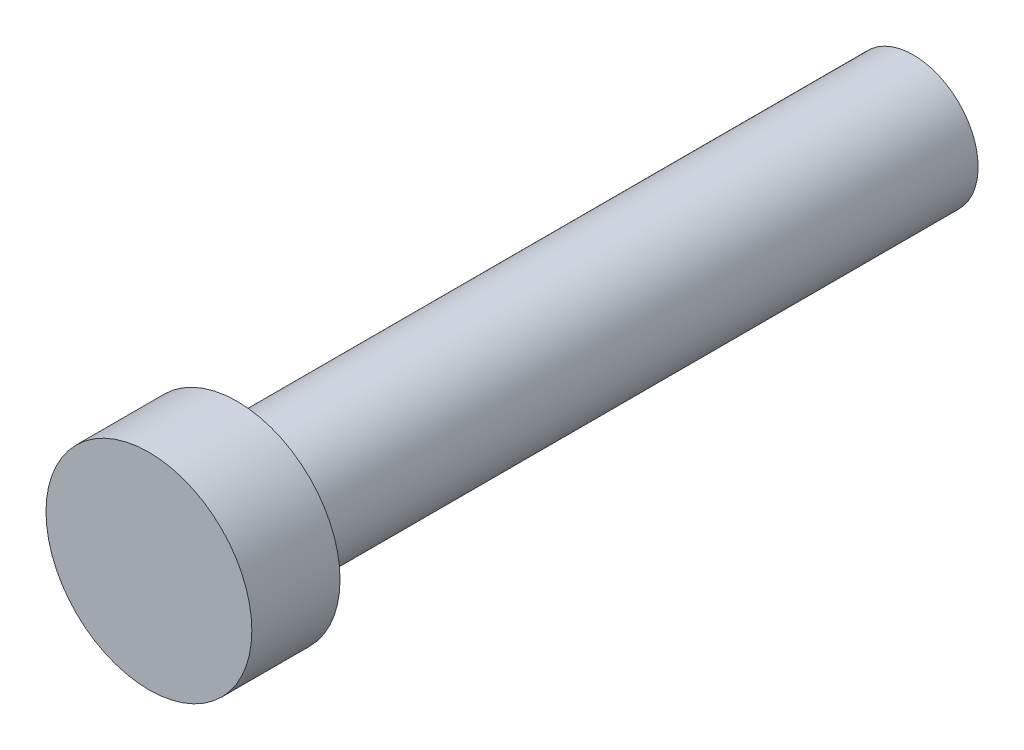
SolidWorks part; units mm, degrees
ref_plane "Front Plane" through (0, 0, 0) normal (0, 0, 1) x (1, 0, 0)
ref_plane "Top Plane" through (0, 0, 0) normal (0, 1, 0) x (1, 0, 0)
ref_plane "Right Plane" through (0, 0, 0) normal (1, 0, 0) x (0, 0, -1)
sketch "Sketch1" plane through (0, 0, 0) normal (0, 0, 1) x (1, 0, 0)
  circle A0 centre (0, 0) radius 2.2
  dimension "D1" = 4.4
extrude "Boss-Extrude1" add sketch "Sketch1" along normal blind 26
sketch "Sketch2" plane through (0, 0, 26) normal (0, 0, 1) x (1, 0, 0)
  circle A0 centre (0, 0) radius 3.5
  dimension "D1" = 7
extrude "Boss-Extrude2" add sketch "Sketch2" against normal blind 3
sketch "Sketch3" plane through (0, 0, 0) normal (0, 0, -1) x (-1, 0, 0)
  circle A0 centre (0, 0) radius 1
  dimension "D1" = 2
extrude "Cut-Extrude1" cut sketch "Sketch3" against normal blind 5
